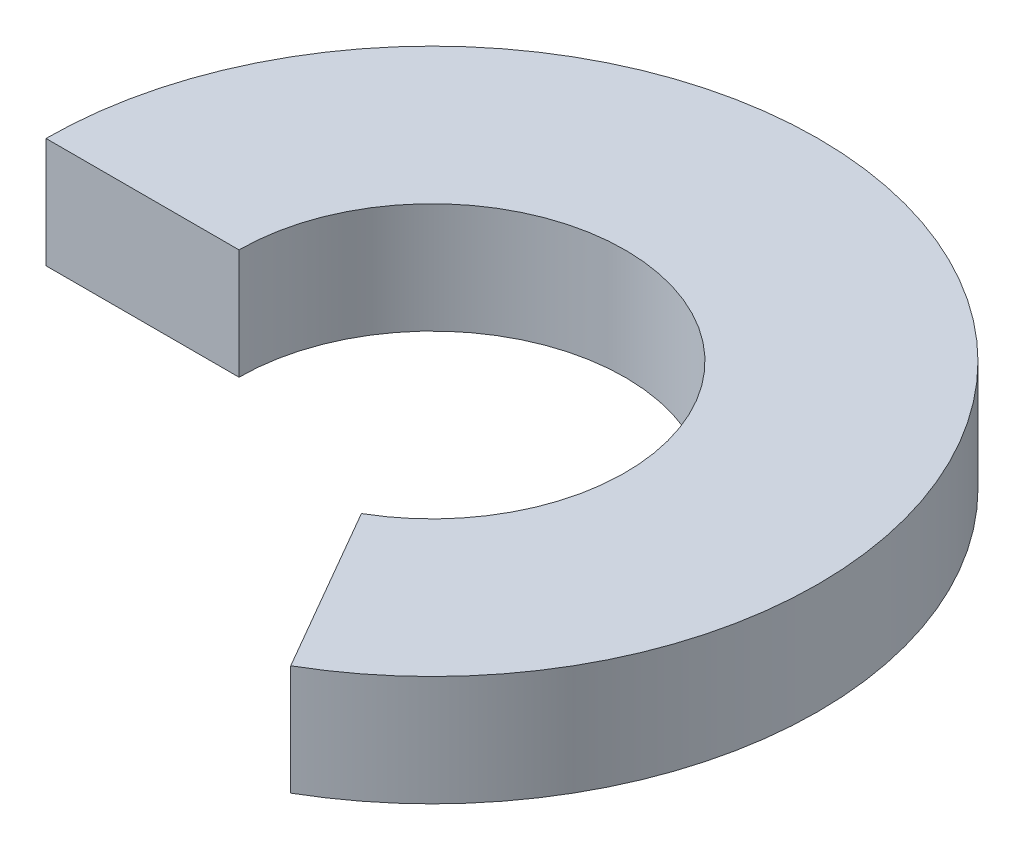
SolidWorks part; units mm, degrees
ref_plane "Front Plane" through (0, 0, 0) normal (0, 0, 1) x (1, 0, 0)
ref_plane "Top Plane" through (0, 0, 0) normal (0, 1, 0) x (1, 0, 0)
ref_plane "Right Plane" through (0, 0, 0) normal (1, 0, 0) x (0, 0, -1)
sketch "Sketch1" plane through (0, 0, 0) normal (0, 1, 0) x (1, 0, 0)
  line L0 (-7, 0) -> (-3.5, 0)
  line L1 (1.75, -3.0311) -> (3.5, -6.0622)
  arc A1 (-3.5, 0) -> (1.75, -3.0311) centre (0, 0) cw
  arc A2 (-7, 0) -> (3.5, -6.0622) centre (0, 0) cw
  dimension "D1" = 3.5
  dimension "D3" = 120
  dimension "D2" = 3.5
extrude "Boss-Extrude1" add sketch "Sketch1" along normal blind 2
